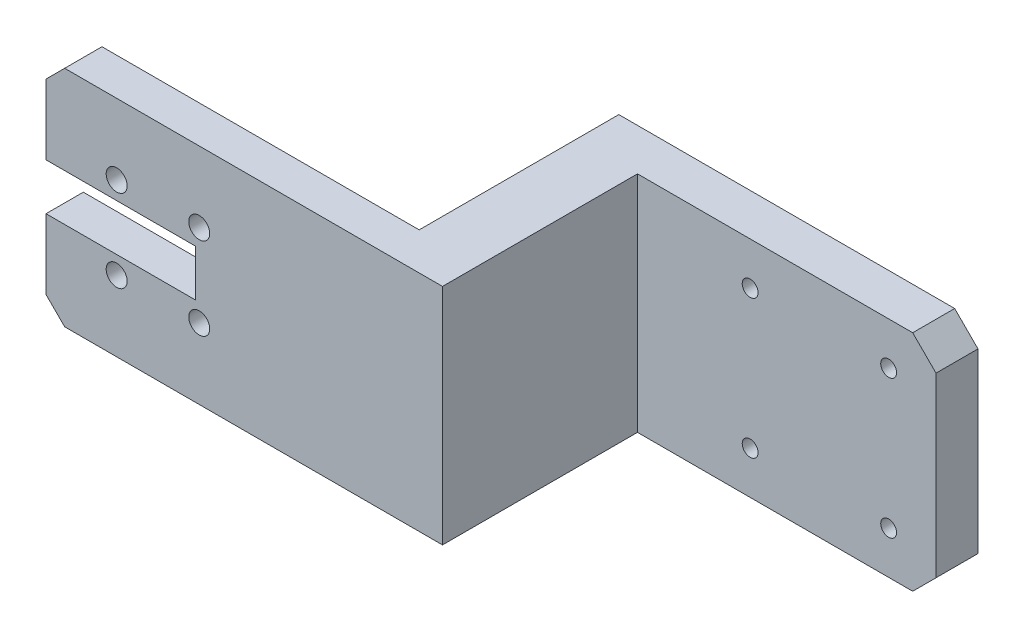
SolidWorks part; units mm, degrees
ref_plane "前视基准面" through (0, 0, 0) normal (0, 0, 1) x (1, 0, 0)
ref_plane "上视基准面" through (0, 0, 0) normal (0, 1, 0) x (1, 0, 0)
ref_plane "右视基准面" through (0, 0, 0) normal (1, 0, 0) x (0, 0, -1)
other "Configuration Table"
sketch "草图1" plane through (0, 0, 0) normal (0, 0, 1) x (1, 0, 0)
  line L0 (48, -24) -> (120, -24)
  line L1 (120, -24) -> (125, -19)
  line L2 (125, -19) -> (125, 19)
  line L3 (125, 19) -> (120, 24)
  line L4 (120, 24) -> (48, 24)
  line L5 (48, 24) -> (48, -24)
  circle A0 centre (85.155, -14.845) radius 3.75
  circle A1 centre (85.155, 14.845) radius 3.75
  circle A2 centre (114.845, -14.845) radius 3.75
  circle A3 centre (114.845, 14.845) radius 3.75
extrude "肘部托板底层和螺钉头避空" add sketch "草图1" along normal blind 4 from offset 0
sketch "草图2" plane through (0, 0, 0) normal (0, 0, 1) x (1, 0, 0)
  line L0 (48, -24) -> (120, -24)
  line L1 (120, -24) -> (125, -19)
  line L2 (125, -19) -> (125, 19)
  line L3 (125, 19) -> (120, 24)
  line L4 (120, 24) -> (48, 24)
  line L5 (48, 24) -> (48, -24)
  circle A0 centre (85.155, -14.845) radius 1.7
  circle A1 centre (85.155, 14.845) radius 1.7
  circle A2 centre (114.845, -14.845) radius 1.7
  circle A3 centre (114.845, 14.845) radius 1.7
extrude "肘部托板顶层与安装孔" add sketch "草图2" along normal blind 5 from offset 4
sketch "草图3" plane through (0, 0, 0) normal (0, 0, 1) x (1, 0, 0)
  line L0 (48, -24) -> (61, -24)
  line L1 (61, -24) -> (61, 24)
  line L2 (61, 24) -> (48, 24)
  line L3 (48, 24) -> (48, -24)
extrude "下沉立壁" add sketch "草图3" along normal blind 33.8 from offset 9
sketch "草图4" plane through (0, 0, 0) normal (0, 0, 1) x (1, 0, 0)
  line L0 (-24, -20) -> (-20, -24)
  line L1 (-20, -24) -> (61, -24)
  line L2 (61, -24) -> (61, 24)
  line L3 (61, 24) -> (-20, 24)
  line L4 (-20, 24) -> (-24, 20)
  line L5 (-24, 20) -> (-24, 5)
  line L6 (-24, 5) -> (8, 5)
  line L7 (8, 5) -> (8, -5)
  line L8 (8, -5) -> (-24, -5)
  line L9 (-24, -5) -> (-24, -20)
  circle A0 centre (-8.85, -8.85) radius 2.25
  circle A1 centre (-8.85, 8.85) radius 2.25
  circle A2 centre (8.85, -8.85) radius 2.25
  circle A3 centre (8.85, 8.85) radius 2.25
extrude "肩端连接板与穿线槽" add sketch "草图4" along normal blind 8 from offset 42.8
